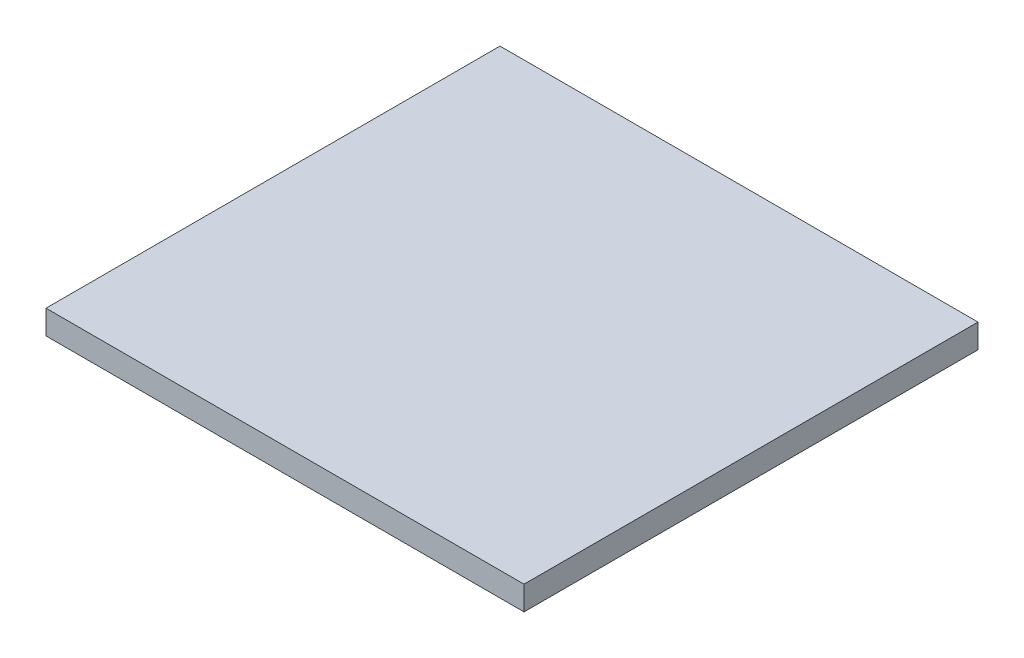
SolidWorks part; units mm, degrees
ref_plane "Alzado" through (0, 0, 0) normal (0, 0, 1) x (1, 0, 0)
ref_plane "Planta" through (0, 0, 0) normal (0, 1, 0) x (1, 0, 0)
ref_plane "Vista lateral" through (0, 0, 0) normal (1, 0, 0) x (0, 0, -1)
sketch "Croquis1" plane through (0, 0, 0) normal (0, 1, 0) x (1, 0, 0)
  line L1 (-179, 170) -> (179, 170)
  line L2 (-179, 170) -> (-179, -170)
  line L3 (-179, -170) -> (179, -170)
  line L4 (179, 170) -> (179, -170)
  line L5 (-179, 170) -> (179, -170) construction
  line L6 (-179, -170) -> (179, 170) construction
  point P0 (0, 0)
  dimension "D1" = 358
  dimension "D2" = 340
extrude "Saliente-Extruir1" add sketch "Croquis1" along normal blind 18
